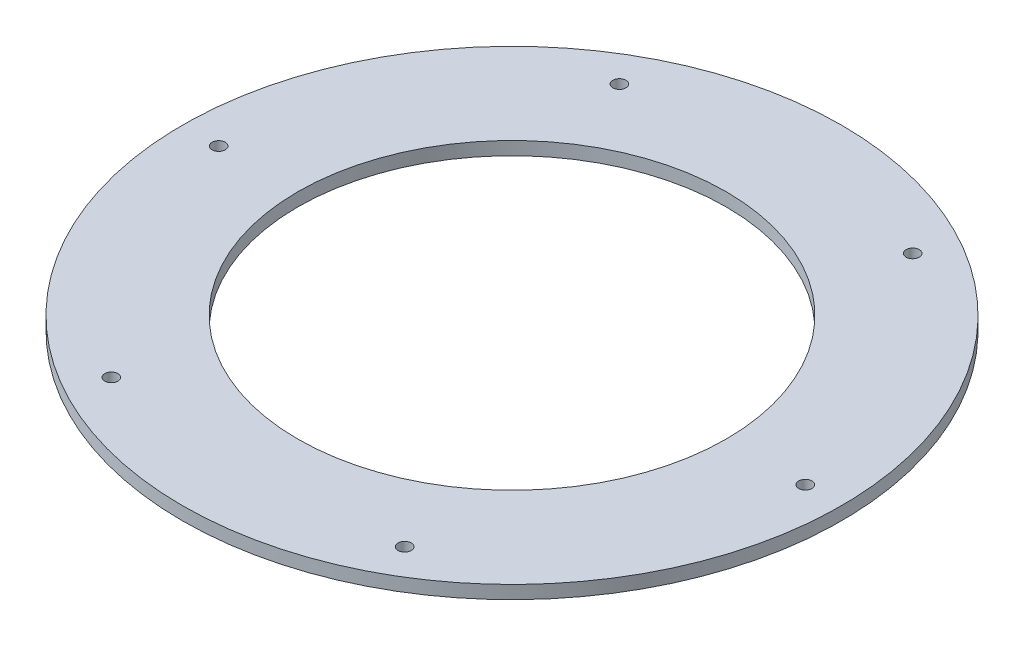
SolidWorks part; units mm, degrees
material "AISI 316 Stainless Steel Sheet (SS)"
ref_plane "Front Plane" through (0, 0, 0) normal (0, 0, 1) x (1, 0, 0)
ref_plane "Top Plane" through (0, 0, 0) normal (0, 1, 0) x (1, 0, 0)
ref_plane "Right Plane" through (0, 0, 0) normal (1, 0, 0) x (0, 0, -1)
sketch "Sketch1" plane through (0, 0, 0) normal (0, 1, 0) x (1, 0, 0)
  circle A0 centre (0, 0) radius 162.5
  circle A1 centre (0, 0) radius 250
  dimension "D1" = 500
  dimension "D2" = 325
extrude "Boss-Extrude1" add sketch "Sketch1" along normal mid plane 10
sketch "Sketch2" plane through (0, 5, 0) normal (0, 1, 0) x (1, 0, 0)
  line L0 (0, -1000) -> (0, 49000) construction
  line L1 (-1000, 0) -> (49000, 0) construction
  line L2 (-500, -866.0254) -> (24500, 42435.2448) construction
  line L3 (-500, 866.0254) -> (24500, -42435.2448) construction
  circle A0 centre (0, 0) radius 222.5 construction
  circle A1 centre (111.25, 192.6907) radius 5
  circle A2 centre (222.5, 0) radius 5
  circle A3 centre (-111.25, 192.6907) radius 5
  circle A4 centre (-222.5, 0) radius 5
  circle A5 centre (111.25, -192.6907) radius 5
  circle A6 centre (-111.25, -192.6907) radius 5
  dimension "D3" = 10
  dimension "D4" = 10
  dimension "D6" = 222.5
  dimension "D1" = 60
  dimension "D2" = 120
  dimension "D5" = 60
extrude "Cut-Extrude1" cut sketch "Sketch2" against normal through all
